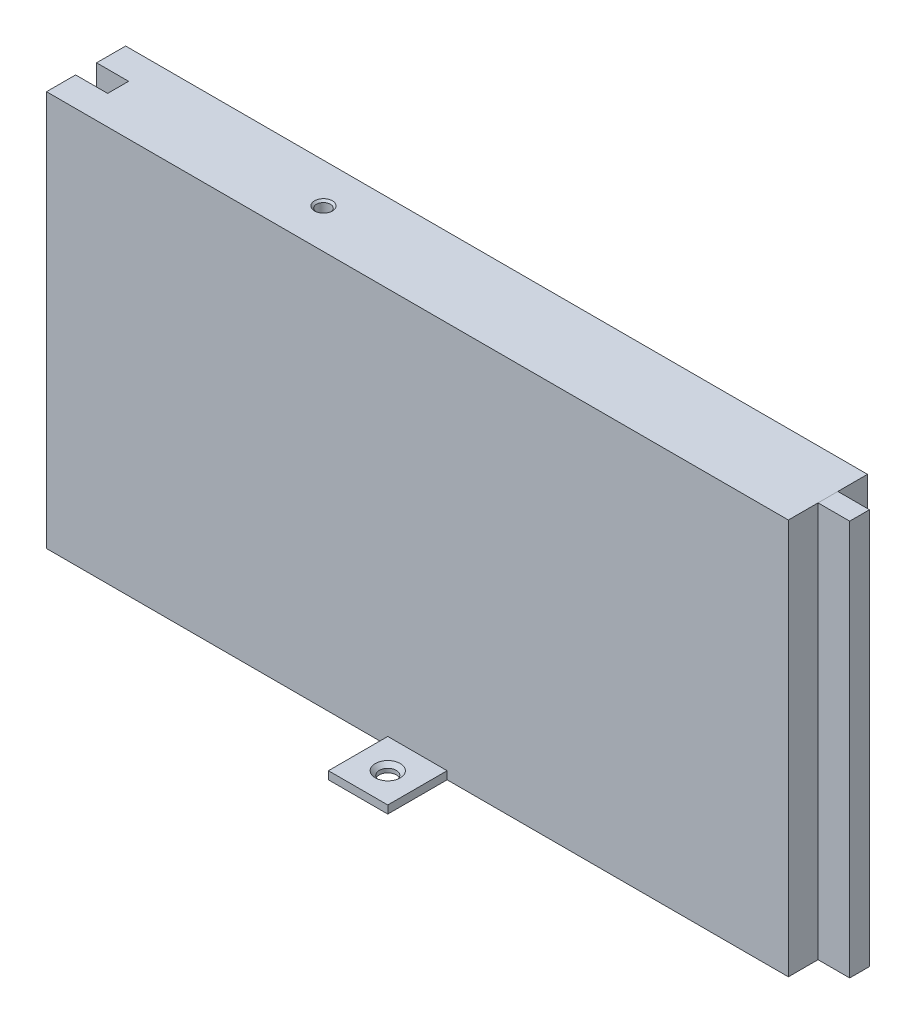
SolidWorks part; units mm, degrees
ref_plane "Front Plane" through (0, 0, 0) normal (0, 0, 1) x (1, 0, 0)
ref_plane "Top Plane" through (0, 0, 0) normal (0, 1, 0) x (1, 0, 0)
ref_plane "Right Plane" through (0, 0, 0) normal (1, 0, 0) x (0, 0, -1)
sketch "Sketch1" plane through (0, 0, 0) normal (0, 1, 0) x (1, 0, 0)
  line L0 (0, 0) -> (0, 20)
  line L1 (0, 20) -> (187.5, 20)
  line L2 (187.5, 20) -> (187.5, 0)
  line L3 (187.5, 0) -> (0, 0)
  dimension "D1" = 20
extrude "Boss-Extrude1" add sketch "Sketch1" along normal blind 100
sketch "Sketch2" plane through (0, 100, 0) normal (0, 1, 0) x (1, 0, 0)
  line L0 (0, 12.65) -> (8.1, 12.65)
  line L1 (0, 20) -> (0, 0) construction
  line L2 (8.1, 12.65) -> (8.1, 7.35)
  line L3 (8.1, 7.35) -> (0, 7.35)
  line L4 (0, 7.35) -> (0, 12.65)
  line L5 (0, 0) -> (187.5, 0) construction
  dimension "D1" = 7.35
  dimension "D2" = 5.3
  dimension "D3" = 8.1
extrude "Cut-Extrude1" cut sketch "Sketch2" against normal blind 100
sketch "Sketch4" plane through (0, 100, 0) normal (0, 1, 0) x (1, 0, 0)
  line L0 (187.5, 12.5) -> (195.5, 12.5)
  line L1 (187.5, 0) -> (187.5, 20) construction
  line L2 (195.5, 12.5) -> (195.5, 7.5)
  line L3 (195.5, 7.5) -> (187.5, 7.5)
  line L4 (187.5, 7.5) -> (187.5, 12.5)
  line L5 (0, 0) -> (187.5, 0) construction
  dimension "D1" = 8
  dimension "D2" = 5
  dimension "D3" = 7.5
extrude "Boss-Extrude2" add sketch "Sketch4" against normal blind 100 separate body
sketch "Sketch5" plane through (0, 100, 0) normal (0, 1, 0) x (1, 0, 0)
  line L0 (0, 7.35) -> (0, 0) construction
  line L1 (187.5, 20) -> (0, 20) construction
  circle A0 centre (60, 10) radius 1.75
  dimension "D1" = 3.5
  dimension "D2" = 60
  dimension "D3" = 10
extrude "Cut-Extrude2" cut sketch "Sketch5" against normal blind 8
chamfer "Chamfer2" distance 0.5 angle 45 1 edges at (60, 100, -8.25)
sketch "Sketch6" plane through (0, 0, -20) normal (0, 0, -1) x (-1, 0, 0)
  line L11 (-101.25, 2) -> (-86.25, 2)
  line L12 (-86.25, 2) -> (-86.25, 0)
  line L13 (-187.5, 0) -> (0, 0) construction
  line L14 (-101.25, 2) -> (-101.25, 0)
  line L15 (0, 100) -> (0, 0) construction
  line L19 (-101.25, 0) -> (-86.25, 0)
  dimension "D1" = 15
  dimension "D2" = 86.25
  dimension "D3" = 2
extrude "Boss-Extrude3" add sketch "Sketch6" along normal blind 15
sketch "Sketch7" plane through (0, 0, 0) normal (0, 0, 1) x (1, 0, 0)
  line L0 (86.25, 2) -> (101.25, 2)
  line L1 (101.25, 2) -> (101.25, 0)
  line L2 (0, 0) -> (187.5, 0) construction
  line L3 (86.25, 2) -> (86.25, 0)
  line L4 (187.5, 0) -> (187.5, 100) construction
  line L5 (86.25, 0) -> (101.25, 0)
  dimension "D1" = 15
  dimension "D2" = 86.25
  dimension "D3" = 2
extrude "Boss-Extrude4" add sketch "Sketch7" along normal blind 15
sketch "Sketch8" plane through (0, 2, 0) normal (0, 1, 0) x (1, 0, 0)
  line L0 (86.25, 35) -> (86.25, 20) construction
  line L1 (86.25, 35) -> (101.25, 35) construction
  line L2 (86.25, -15) -> (86.25, 0) construction
  line L3 (101.25, -15) -> (86.25, -15) construction
  circle A0 centre (93.75, 27.5) radius 2.15
  circle A1 centre (93.75, -7.5) radius 2.15
  dimension "D1" = 4.3
  dimension "D2" = 4.3
  dimension "D3" = 7.5
  dimension "D4" = 7.5
  dimension "D5" = 7.5
  dimension "D6" = 7.5
extrude "Cut-Extrude3" cut sketch "Sketch8" against normal blind 15
chamfer "Chamfer3" distance 1 angle 45 2 edges at (91.6, 2, 7.5) (91.6, 2, -27.5)
